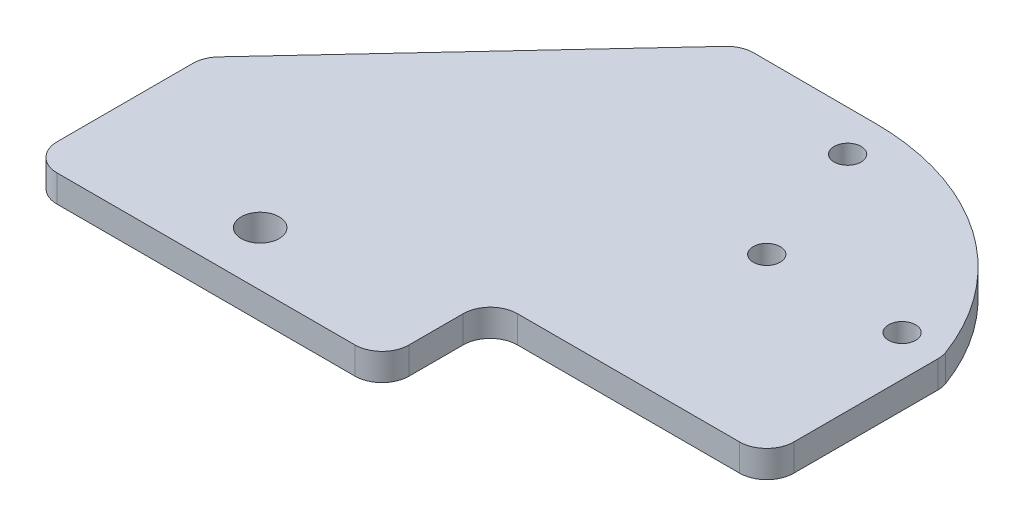
SolidWorks part; units mm, degrees
material "6061 Alloy"
ref_plane "Front Plane" through (0, 0, 0) normal (0, 0, 1) x (1, 0, 0)
ref_plane "Top Plane" through (0, 0, 0) normal (0, 1, 0) x (1, 0, 0)
ref_plane "Right Plane" through (0, 0, 0) normal (1, 0, 0) x (0, 0, -1)
sketch "Sketch1" plane through (0, 0, 0) normal (0, 1, 0) x (1, 0, 0)
  line L1 (-1.5452, 127) -> (10, 127)
  line L2 (5, 0) -> (87.1, 0)
  line L3 (97.1, 10) -> (97.1, 63.2668)
  line L4 (0, 25) -> (97.1, 25) construction
  line L5 (0, 25) -> (-135, 20.1354) construction
  line L6 (-5, -10) -> (-5, -30)
  line L7 (-15, -40) -> (-125, -40)
  line L8 (-135, -30) -> (-135, 20.1354)
  line L9 (-132.3211, 26.9473) -> (-42.1194, 123.8926)
  line L10 (-34.774, 127.0807) -> (-1.5452, 127)
  arc A0 (10, 127) -> (96.4818, 66.7284) centre (10, 34.8193) cw
  arc A1 (96.4818, 66.7284) -> (97.1, 63.2668) centre (87.1, 63.2668) cw
  arc A2 (87.1, 0) -> (97.1, 10) centre (87.1, 10) ccw
  arc A3 (-5, -10) -> (5, 0) centre (5, -10) cw
  arc A4 (-15, -40) -> (-5, -30) centre (-15, -30) ccw
  arc A5 (-125, -40) -> (-135, -30) centre (-125, -30) cw
  arc A6 (-135, 20.1354) -> (-132.3211, 26.9473) centre (-125, 20.1354) cw
  arc A7 (-42.1194, 123.8926) -> (-34.774, 127.0807) centre (-34.7983, 117.0808) cw
  point P19 (97.1, 65)
  point P23 (97.1, 0)
  point P26 (-5, 0)
  point P29 (-5, -40)
  point P32 (-135, -40)
  point P35 (-135, 24.0681)
  point P38 (-5, 127)
  dimension "D1" = 10
  dimension "D7" = 10
  dimension "D2" = 127
  dimension "D3" = 15
  dimension "D4" = 65
  dimension "D5" = 25
  dimension "D6" = 45
sketch "Sketch2" plane through (0, 0, 0) normal (0, 1, 0) x (1, 0, 0)
  line L0 (14.999, 111.9846) -> (32.1, 65) construction
  line L1 (32.1, 65) -> (82.1, 65) construction
  line L2 (32.1, 65) -> (42.3606, 36.8092) construction
  line L3 (30.6144, 32.534) -> (54.1068, 41.0845) construction
  line L4 (0, 25) -> (97.1, 25) construction
  circle A0 centre (14.999, 111.9846) radius 5
  circle A1 centre (82.1, 65) radius 5
  circle A2 centre (32.1, 65) radius 5
  point P9 (42.3606, 36.8092)
  dimension "D1" = 50
  dimension "D2" = 50
  dimension "D4" = 110
  dimension "D5" = 7.534
extrude "Boss-Extrude1" add sketch "Sketch1" along normal blind 10
extrude "Cut-Extrude4" cut sketch "Sketch2" against normal through all and the other way through all
sketch "Sketch3" plane through (0, 0, 0) normal (0, -1, 0) x (1, 0, 0)
  line L0 (-125, 40) -> (-15, 40) construction
  line L1 (-70, 20) -> (-135, 20) construction
  line L2 (-135, -20.1354) -> (-135, 30) construction
  line L3 (-70, 20) -> (-5, 20) construction
  line L4 (-5, 30) -> (-5, 10) construction
  circle A0 centre (-70, 20) radius 7
  point P4 (-66.6328, 20)
  point P9 (-5, 20)
  dimension "D1" = 20
extrude "Cut-Extrude5" cut sketch "Sketch3" against normal through all
